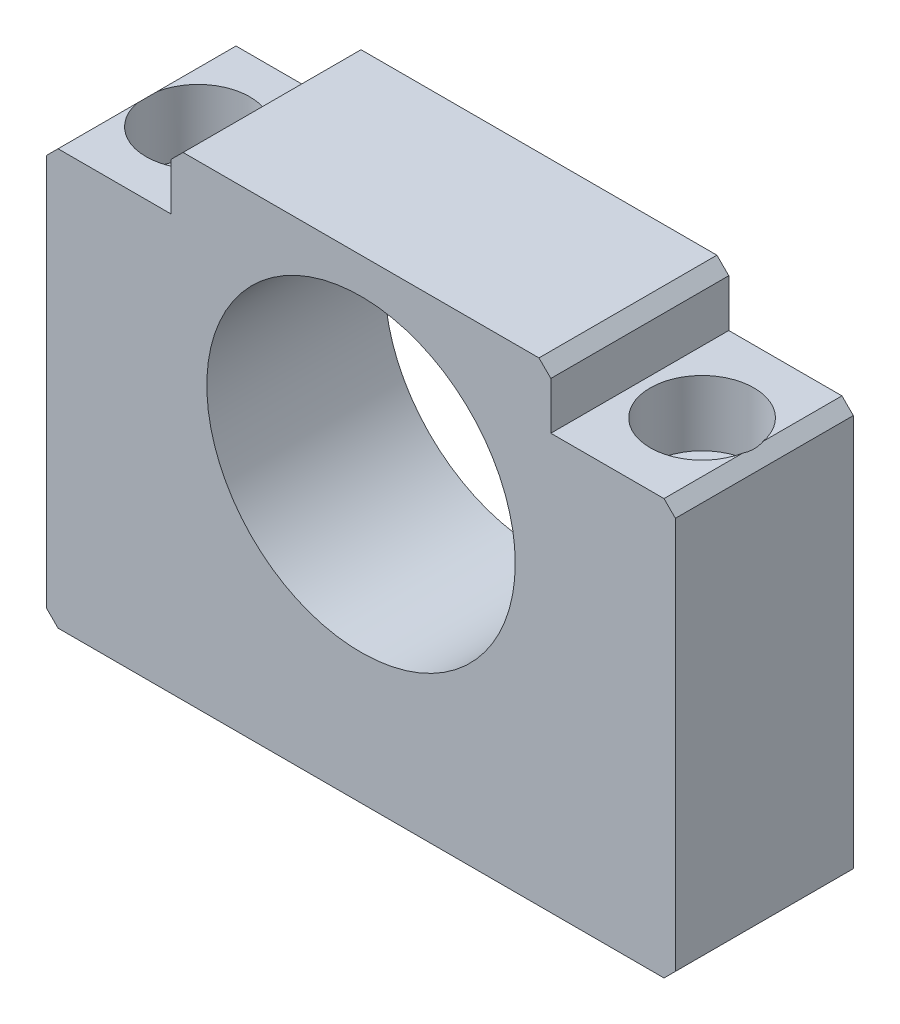
SolidWorks part; units mm, degrees
material "Low Carbon Steel"
ref_plane "Front Plane" through (0, 0, 0) normal (0, 0, 1) x (1, 0, 0)
ref_plane "Top Plane" through (0, 0, 0) normal (0, 1, 0) x (1, 0, 0)
ref_plane "Right Plane" through (0, 0, 0) normal (1, 0, 0) x (0, 0, -1)
ref_plane "Plane1" through (0, 0, 0) normal (0, 0, 1) x (1, 0, 0)
sketch "Sketch1" plane through (0, 0, 0) normal (0, 0, 1) x (1, 0, 0)
  line L0 (-53, -46.08) -> (-51.08, -48)
  line L1 (-51.08, -48) -> (51.08, -48)
  line L2 (51.08, -48) -> (53, -46.08)
  line L3 (53, -46.08) -> (53, 20.08)
  line L4 (53, 20.08) -> (51.08, 22)
  line L5 (51.08, 22) -> (32, 22)
  line L6 (32, 22) -> (32, 30)
  line L7 (32, 30) -> (30, 32)
  line L8 (30, 32) -> (-30, 32)
  line L9 (-30, 32) -> (-32, 30)
  line L10 (-32, 30) -> (-32, 22)
  line L11 (-32, 22) -> (-51.08, 22)
  line L12 (-51.08, 22) -> (-53, 20.08)
  line L13 (-53, 20.08) -> (-53, -46.08)
extrude "Boss-Extrude1" add sketch "Sketch1" against normal blind 30
ref_plane "Plane2" through (42.5, 0, 0) normal (1, 0, 0) x (0, 0, -1)
sketch "Sketch2" plane through (42.5, 0, 0) normal (1, 0, 0) x (0, 0, -1)
  line L0 (15, 22) -> (23.75, 22)
  line L1 (23.75, 22) -> (23.75, 11)
  line L2 (23.75, 11) -> (20.5, 11)
  line L3 (20.5, 11) -> (20.5, -48)
  line L4 (20.5, -48) -> (15, -48)
  line L5 (15, -48) -> (15, 22)
  line L6 (15, -48) -> (15, 22) construction
revolve "Cut-Revolve1" cut sketch "Sketch2" angle 360 about L6
ref_plane "Plane3" through (-42.5, 0, 0) normal (1, 0, 0) x (0, 0, -1)
sketch "Sketch3" plane through (-42.5, 0, 0) normal (1, 0, 0) x (0, 0, -1)
  line L0 (15, 22) -> (23.75, 22)
  line L1 (23.75, 22) -> (23.75, 11)
  line L2 (23.75, 11) -> (20.5, 11)
  line L3 (20.5, 11) -> (20.5, -48)
  line L4 (20.5, -48) -> (15, -48)
  line L5 (15, -48) -> (15, 22)
  line L6 (15, -48) -> (15, 22) construction
revolve "Cut-Revolve2" cut sketch "Sketch3" angle 360 about L6
ref_plane "Plane4" through (0, 0, 0) normal (0, 0, 1) x (1, 0, 0)
sketch "Sketch4" plane through (0, 0, 0) normal (0, 0, 1) x (1, 0, 0)
  circle A0 centre (0, 0) radius 26
extrude "Cut-Extrude1" cut sketch "Sketch4" against normal blind 30
other "Freeze***"
